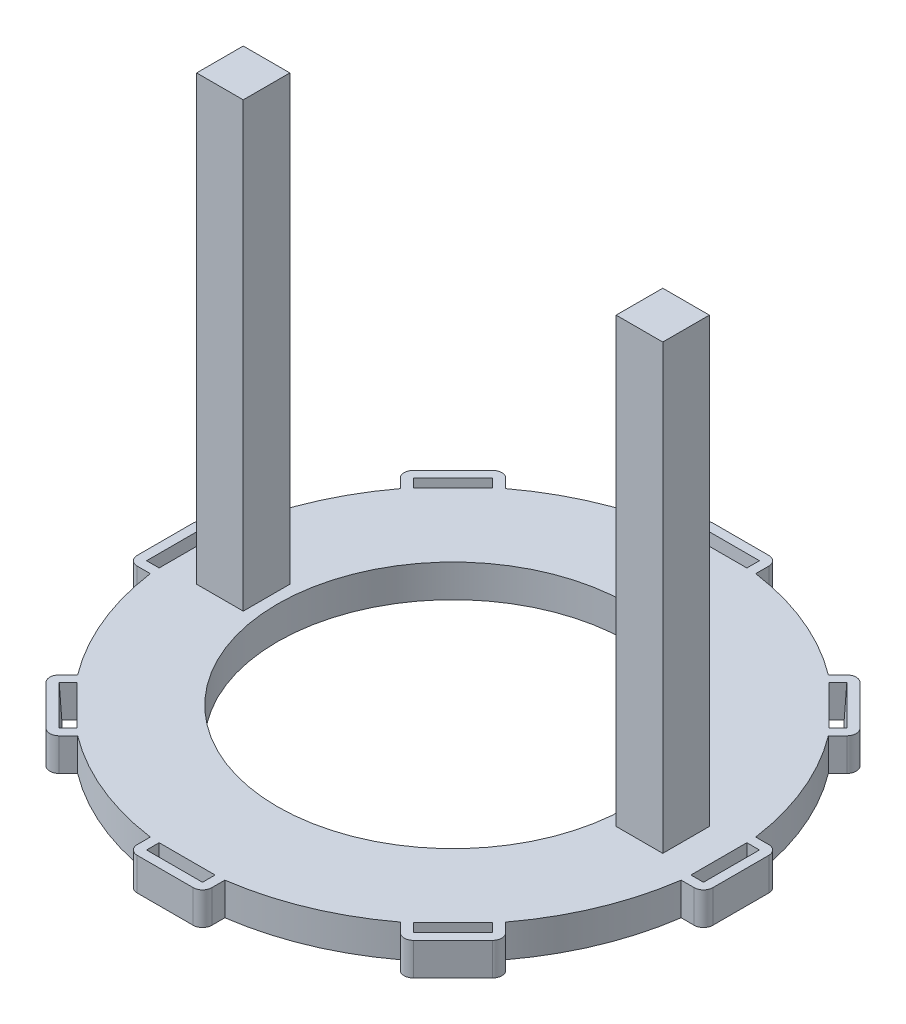
SolidWorks part; units mm, degrees
ref_plane "Front Plane" through (0, 0, 0) normal (0, 0, 1) x (1, 0, 0)
ref_plane "Top Plane" through (0, 0, 0) normal (0, 1, 0) x (1, 0, 0)
ref_plane "Right Plane" through (0, 0, 0) normal (1, 0, 0) x (0, 0, -1)
sketch "Sketch1" plane through (0, 0, 0) normal (0, 1, 0) x (1, 0, 0)
  line L0 (-8, 56.9408) -> (-8, 59.7408)
  line L1 (0, 57.5) -> (0, -57.5) construction
  line L2 (8, 56.9408) -> (8, 59.7408)
  line L3 (-6, 61.7408) -> (6, 61.7408)
  line L4 (39.4147, 47.8999) -> (47.8999, 39.4147)
  line L9 (34.6063, 45.9201) -> (36.5862, 47.8999)
  line L10 (45.9201, 34.6063) -> (47.8999, 36.5862)
  line L15 (61.7408, 6) -> (61.7408, -6)
  line L16 (56.9408, 8) -> (59.7408, 8)
  line L17 (56.9408, -8) -> (59.7408, -8)
  line L22 (47.8999, -39.4147) -> (39.4147, -47.8999)
  line L23 (45.9201, -34.6063) -> (47.8999, -36.5862)
  line L24 (34.6063, -45.9201) -> (36.5862, -47.8999)
  line L29 (6, -61.7408) -> (-6, -61.7408)
  line L30 (8, -56.9408) -> (8, -59.7408)
  line L31 (-8, -56.9408) -> (-8, -59.7408)
  line L36 (-39.4147, -47.8999) -> (-47.8999, -39.4147)
  line L37 (-34.6063, -45.9201) -> (-36.5862, -47.8999)
  line L38 (-45.9201, -34.6063) -> (-47.8999, -36.5862)
  line L43 (-61.7408, -6) -> (-61.7408, 6)
  line L44 (-56.9408, -8) -> (-59.7408, -8)
  line L45 (-56.9408, 8) -> (-59.7408, 8)
  line L50 (-47.8999, 39.4147) -> (-39.4147, 47.8999)
  line L51 (-45.9201, 34.6063) -> (-47.8999, 36.5862)
  line L52 (-34.6063, 45.9201) -> (-36.5862, 47.8999)
  arc A0 (-8, 56.9408) -> (-34.6063, 45.9201) centre (0, 0) ccw
  arc A1 (6, 61.7408) -> (8, 59.7408) centre (6, 59.7408) cw
  arc A2 (-6, 61.7408) -> (-8, 59.7408) centre (-6, 59.7408) ccw
  arc A3 (39.4147, 47.8999) -> (36.5862, 47.8999) centre (38.0005, 46.4857) ccw
  arc A4 (47.8999, 39.4147) -> (47.8999, 36.5862) centre (46.4857, 38.0005) cw
  arc A5 (61.7408, 6) -> (59.7408, 8) centre (59.7408, 6) ccw
  arc A6 (61.7408, -6) -> (59.7408, -8) centre (59.7408, -6) cw
  arc A7 (47.8999, -39.4147) -> (47.8999, -36.5862) centre (46.4857, -38.0005) ccw
  arc A8 (39.4147, -47.8999) -> (36.5862, -47.8999) centre (38.0005, -46.4857) cw
  arc A9 (6, -61.7408) -> (8, -59.7408) centre (6, -59.7408) ccw
  arc A10 (-6, -61.7408) -> (-8, -59.7408) centre (-6, -59.7408) cw
  arc A11 (-39.4147, -47.8999) -> (-36.5862, -47.8999) centre (-38.0005, -46.4857) ccw
  arc A12 (-47.8999, -39.4147) -> (-47.8999, -36.5862) centre (-46.4857, -38.0005) cw
  arc A13 (-61.7408, -6) -> (-59.7408, -8) centre (-59.7408, -6) ccw
  arc A14 (-61.7408, 6) -> (-59.7408, 8) centre (-59.7408, 6) cw
  arc A15 (-47.8999, 39.4147) -> (-47.8999, 36.5862) centre (-46.4857, 38.0005) ccw
  arc A16 (-39.4147, 47.8999) -> (-36.5862, 47.8999) centre (-38.0005, 46.4857) cw
  arc A17 (-45.9201, 34.6063) -> (-56.9408, 8) centre (0, 0) ccw
  arc A18 (-56.9408, -8) -> (-45.9201, -34.6063) centre (0, 0) ccw
  arc A19 (34.6063, 45.9201) -> (8, 56.9408) centre (0, 0) ccw
  arc A20 (-34.6063, -45.9201) -> (-8, -56.9408) centre (0, 0) ccw
  arc A21 (8, -56.9408) -> (34.6063, -45.9201) centre (0, 0) ccw
  arc A22 (45.9201, -34.6063) -> (56.9408, -8) centre (0, 0) ccw
  arc A23 (56.9408, 8) -> (45.9201, 34.6063) centre (0, 0) ccw
  point P11 (8, 61.7408)
  point P14 (-8, 61.7408)
  point P17 (-8, 58.3408)
  point P98 (0, 0)
  dimension "D1" = 115
  dimension "D2" = 2
  dimension "D3" = 16
  dimension "D4" = 2.8
  dimension "D7" = 8
extrude "Boss-Extrude1" add sketch "Sketch1" along normal blind 7
sketch "Sketch2" plane through (0, 7, 0) normal (0, 1, 0) x (1, 0, 0)
  line L0 (-57.5, 0) -> (57.5, 0) construction
  line L1 (0, 57.5) -> (0, -57.5) construction
  line L2 (40, 5) -> (50, 5)
  line L3 (40, 5) -> (40, -5)
  line L4 (40, -5) -> (50, -5)
  line L5 (50, 5) -> (50, -5)
  line L6 (40, 5) -> (50, -5) construction
  line L7 (40, -5) -> (50, 5) construction
  line L8 (-40, -5) -> (-50, -5)
  line L9 (-50, 5) -> (-50, -5)
  line L10 (-40, 5) -> (-50, 5)
  line L11 (-40, 5) -> (-40, -5)
  circle A0 centre (0, 0) radius 57.5 construction
  point P5 (45, 0)
  point P16 (-45, 0)
  point P22 (-45, -5)
  dimension "D1" = 10
  dimension "D2" = 10
  dimension "D3" = 80
extrude "Boss-Extrude2" add sketch "Sketch2" along normal blind 95
sketch "Sketch3" plane through (0, 7, 0) normal (0, 1, 0) x (1, 0, 0)
  circle A0 centre (0, 0) radius 37.6637
extrude "Cut-Extrude1" cut sketch "Sketch3" against normal through all
sketch "Sketch5" plane through (0, 7, 0) normal (0, 1, 0) x (1, 0, 0)
  line L1 (-6, 59.7408) -> (6, 59.7408)
  line L2 (-6, 59.7408) -> (-6, 57.0408)
  line L3 (-6, 57.0408) -> (6, 57.0408)
  line L4 (6, 59.7408) -> (6, 57.0408)
  line L24 (8, 56.9408) -> (8, 59.7408)
  line L25 (6, 61.7408) -> (-6, 61.7408)
  line L26 (-8, 59.7408) -> (-8, 56.9408)
  line L27 (-34.6063, 45.9201) -> (-36.5862, 47.8999)
  line L28 (-39.4147, 47.8999) -> (-47.8999, 39.4147)
  line L29 (-47.8999, 36.5862) -> (-45.9201, 34.6063)
  line L30 (-56.9408, 8) -> (-59.7408, 8)
  line L31 (-61.7408, 6) -> (-61.7408, -6)
  line L32 (-59.7408, -8) -> (-56.9408, -8)
  line L33 (-45.9201, -34.6063) -> (-47.8999, -36.5862)
  line L34 (-47.8999, -39.4147) -> (-39.4147, -47.8999)
  line L35 (-36.5862, -47.8999) -> (-34.6063, -45.9201)
  line L36 (-8, -56.9408) -> (-8, -59.7408)
  line L37 (-6, -61.7408) -> (6, -61.7408)
  line L38 (8, -59.7408) -> (8, -56.9408)
  line L39 (34.6063, -45.9201) -> (36.5862, -47.8999)
  line L40 (39.4147, -47.8999) -> (47.8999, -39.4147)
  line L41 (47.8999, -36.5862) -> (45.9201, -34.6063)
  line L42 (56.9408, -8) -> (59.7408, -8)
  line L43 (61.7408, -6) -> (61.7408, 6)
  line L44 (59.7408, 8) -> (56.9408, 8)
  line L45 (45.9201, 34.6063) -> (47.8999, 36.5862)
  line L46 (47.8999, 39.4147) -> (39.4147, 47.8999)
  line L47 (36.5862, 47.8999) -> (34.6063, 45.9201)
  line L48 (8, 56.9408) -> (8, 59.7408)
  line L49 (6, 61.7408) -> (-6, 61.7408)
  line L50 (-8, 59.7408) -> (-8, 56.9408)
  line L51 (-34.6063, 45.9201) -> (-36.5862, 47.8999)
  line L52 (-39.4147, 47.8999) -> (-47.8999, 39.4147)
  line L53 (-47.8999, 36.5862) -> (-45.9201, 34.6063)
  line L54 (-56.9408, 8) -> (-59.7408, 8)
  line L55 (-61.7408, 6) -> (-61.7408, -6)
  line L56 (-59.7408, -8) -> (-56.9408, -8)
  line L57 (-45.9201, -34.6063) -> (-47.8999, -36.5862)
  line L58 (-47.8999, -39.4147) -> (-39.4147, -47.8999)
  line L59 (-36.5862, -47.8999) -> (-34.6063, -45.9201)
  line L60 (-8, -56.9408) -> (-8, -59.7408)
  line L61 (-6, -61.7408) -> (6, -61.7408)
  line L62 (8, -59.7408) -> (8, -56.9408)
  line L63 (34.6063, -45.9201) -> (36.5862, -47.8999)
  line L64 (39.4147, -47.8999) -> (47.8999, -39.4147)
  line L65 (47.8999, -36.5862) -> (45.9201, -34.6063)
  line L66 (56.9408, -8) -> (59.7408, -8)
  line L67 (61.7408, -6) -> (61.7408, 6)
  line L68 (59.7408, 8) -> (56.9408, 8)
  line L69 (45.9201, 34.6063) -> (47.8999, 36.5862)
  line L70 (47.8999, 39.4147) -> (39.4147, 47.8999)
  line L71 (36.5862, 47.8999) -> (34.6063, 45.9201)
  arc A24 (34.6063, 45.9201) -> (8, 56.9408) centre (0, 0) ccw
  arc A25 (8, 59.7408) -> (6, 61.7408) centre (6, 59.7408) ccw
  arc A26 (-6, 61.7408) -> (-8, 59.7408) centre (-6, 59.7408) ccw
  arc A27 (-8, 56.9408) -> (-34.6063, 45.9201) centre (0, 0) ccw
  arc A28 (-36.5862, 47.8999) -> (-39.4147, 47.8999) centre (-38.0005, 46.4857) ccw
  arc A29 (-47.8999, 39.4147) -> (-47.8999, 36.5862) centre (-46.4857, 38.0005) ccw
  arc A30 (-45.9201, 34.6063) -> (-56.9408, 8) centre (0, 0) ccw
  arc A31 (-59.7408, 8) -> (-61.7408, 6) centre (-59.7408, 6) ccw
  arc A32 (-61.7408, -6) -> (-59.7408, -8) centre (-59.7408, -6) ccw
  arc A33 (-56.9408, -8) -> (-45.9201, -34.6063) centre (0, 0) ccw
  arc A34 (-47.8999, -36.5862) -> (-47.8999, -39.4147) centre (-46.4857, -38.0005) ccw
  arc A35 (-39.4147, -47.8999) -> (-36.5862, -47.8999) centre (-38.0005, -46.4857) ccw
  arc A36 (-34.6063, -45.9201) -> (-8, -56.9408) centre (0, 0) ccw
  arc A37 (-8, -59.7408) -> (-6, -61.7408) centre (-6, -59.7408) ccw
  arc A38 (6, -61.7408) -> (8, -59.7408) centre (6, -59.7408) ccw
  arc A39 (8, -56.9408) -> (34.6063, -45.9201) centre (0, 0) ccw
  arc A40 (36.5862, -47.8999) -> (39.4147, -47.8999) centre (38.0005, -46.4857) ccw
  arc A41 (47.8999, -39.4147) -> (47.8999, -36.5862) centre (46.4857, -38.0005) ccw
  arc A42 (45.9201, -34.6063) -> (56.9408, -8) centre (0, 0) ccw
  arc A43 (59.7408, -8) -> (61.7408, -6) centre (59.7408, -6) ccw
  arc A44 (61.7408, 6) -> (59.7408, 8) centre (59.7408, 6) ccw
  arc A45 (56.9408, 8) -> (45.9201, 34.6063) centre (0, 0) ccw
  arc A46 (47.8999, 36.5862) -> (47.8999, 39.4147) centre (46.4857, 38.0005) ccw
  arc A47 (39.4147, 47.8999) -> (36.5862, 47.8999) centre (38.0005, 46.4857) ccw
  arc A48 (34.6063, 45.9201) -> (8, 56.9408) centre (0, 0) ccw
  arc A49 (8, 59.7408) -> (6, 61.7408) centre (6, 59.7408) ccw
  arc A50 (-6, 61.7408) -> (-8, 59.7408) centre (-6, 59.7408) ccw
  arc A51 (-8, 56.9408) -> (-34.6063, 45.9201) centre (0, 0) ccw
  arc A52 (-36.5862, 47.8999) -> (-39.4147, 47.8999) centre (-38.0005, 46.4857) ccw
  arc A53 (-47.8999, 39.4147) -> (-47.8999, 36.5862) centre (-46.4857, 38.0005) ccw
  arc A54 (-45.9201, 34.6063) -> (-56.9408, 8) centre (0, 0) ccw
  arc A55 (-59.7408, 8) -> (-61.7408, 6) centre (-59.7408, 6) ccw
  arc A56 (-61.7408, -6) -> (-59.7408, -8) centre (-59.7408, -6) ccw
  arc A57 (-56.9408, -8) -> (-45.9201, -34.6063) centre (0, 0) ccw
  arc A58 (-47.8999, -36.5862) -> (-47.8999, -39.4147) centre (-46.4857, -38.0005) ccw
  arc A59 (-39.4147, -47.8999) -> (-36.5862, -47.8999) centre (-38.0005, -46.4857) ccw
  arc A60 (-34.6063, -45.9201) -> (-8, -56.9408) centre (0, 0) ccw
  arc A61 (-8, -59.7408) -> (-6, -61.7408) centre (-6, -59.7408) ccw
  arc A62 (6, -61.7408) -> (8, -59.7408) centre (6, -59.7408) ccw
  arc A63 (8, -56.9408) -> (34.6063, -45.9201) centre (0, 0) ccw
  arc A64 (36.5862, -47.8999) -> (39.4147, -47.8999) centre (38.0005, -46.4857) ccw
  arc A65 (47.8999, -39.4147) -> (47.8999, -36.5862) centre (46.4857, -38.0005) ccw
  arc A66 (45.9201, -34.6063) -> (56.9408, -8) centre (0, 0) ccw
  arc A67 (59.7408, -8) -> (61.7408, -6) centre (59.7408, -6) ccw
  arc A68 (61.7408, 6) -> (59.7408, 8) centre (59.7408, 6) ccw
  arc A69 (56.9408, 8) -> (45.9201, 34.6063) centre (0, 0) ccw
  arc A70 (47.8999, 36.5862) -> (47.8999, 39.4147) centre (46.4857, 38.0005) ccw
  arc A71 (39.4147, 47.8999) -> (36.5862, 47.8999) centre (38.0005, 46.4857) ccw
  dimension "D2" = 12
  dimension "D3" = 2.7
  dimension "D1" = 0
sketch "Sketch7" plane through (0, 0, 0) normal (0, -1, 0) x (1, 0, 0)
  line L0 (6, -59.7408) -> (6, -57.0408) construction
  line L1 (-6, -57.0408) -> (6, -57.0408)
  line L2 (-6, -57.0408) -> (-6, -59.3408)
  line L3 (-6, -59.3408) -> (6, -59.3408)
  line L4 (6, -57.0408) -> (6, -59.3408)
  dimension "D1" = 2.3
loft "Cut-Loft1" cut profiles "Sketch7" section "Sketch7" section "Sketch5"
sketch "Sketch9" plane through (0, 0, 0) normal (1, 0, 0) x (0, 0, -1)
  line L0 (0, 102) -> (0, 0) construction
  line L1 (-5, 102) -> (5, 102) construction
pattern_circular "CirPattern1" count 8 over 360 about axis through (0, 0, 0) along (0, 1, 0) of "Cut-Loft1"
sketch "Sketch13" plane through (0, 0, -5) normal (0, 0, -1) x (-1, 0, 0)
  line L0 (-45, 102) -> (-45, 7) construction
  line L1 (-50, 102) -> (-40, 102) construction
  line L2 (-50, 7) -> (-40, 7) construction
equation "\"85.00.00mm\"=8500"
